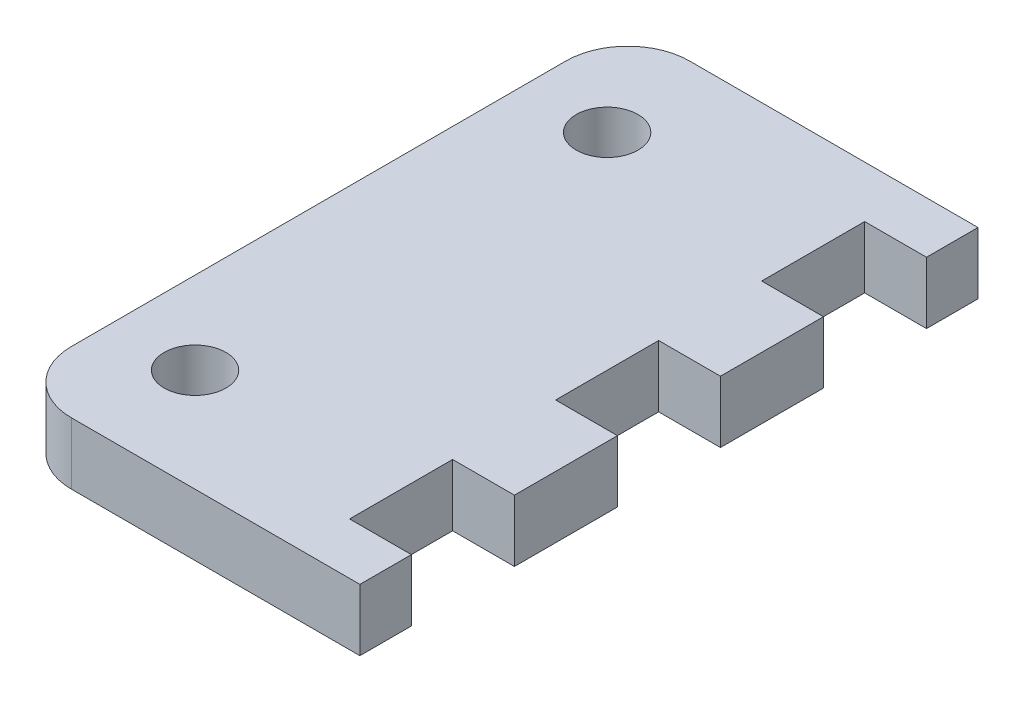
SolidWorks part; units mm, degrees
ref_plane "Front Plane" through (0, 0, 0) normal (0, 0, 1) x (1, 0, 0)
ref_plane "Top Plane" through (0, 0, 0) normal (0, 1, 0) x (1, 0, 0)
ref_plane "Right Plane" through (0, 0, 0) normal (1, 0, 0) x (0, 0, -1)
sketch "Sketch1" plane through (0, 0, 0) normal (0, 1, 0) x (1, 0, 0)
  line L1 (-8.5, 15) -> (8.5, 15)
  line L2 (-8.5, 15) -> (-8.5, -15)
  line L3 (-8.5, -15) -> (8.5, -15)
  line L4 (8.5, 15) -> (8.5, -15)
  line L5 (-8.5, 15) -> (8.5, -15) construction
  line L6 (-8.5, -15) -> (8.5, 15) construction
  point P0 (0, 0)
  dimension "D1" = 17
  dimension "D2" = 30
extrude "Boss-Extrude1" add sketch "Sketch1" along normal blind 3
sketch "Sketch2" plane through (0, 3, 0) normal (0, 1, 0) x (1, 0, 0)
  line L0 (8.5, 12.5) -> (5.5, 12.5)
  line L1 (8.5, -15) -> (8.5, 15) construction
  line L2 (5.5, 12.5) -> (5.5, 7.5)
  line L3 (5.5, 7.5) -> (8.5, 7.5)
  line L4 (8.5, 7.5) -> (8.5, 12.5)
  line L5 (8.5, 15) -> (-8.5, 15) construction
  line L6 (8.5, 2.5) -> (5.5, 2.5)
  line L7 (8.5, 2.5) -> (8.5, -2.5)
  line L8 (8.5, -2.5) -> (5.5, -2.5)
  line L9 (5.5, 2.5) -> (5.5, -2.5)
  line L10 (8.5, -7.5) -> (5.5, -7.5)
  line L11 (8.5, -7.5) -> (8.5, -12.5)
  line L12 (8.5, -12.5) -> (5.5, -12.5)
  line L13 (5.5, -7.5) -> (5.5, -12.5)
  line L14 (-8.5, -15) -> (8.5, -15) construction
  point P14 (5.5, 0)
  point P17 (5.5, 10)
  point P18 (5.5, -10)
  dimension "D1" = 5
  dimension "D2" = 5
  dimension "D3" = 5
  dimension "D4" = 15
  dimension "D5" = 5
  dimension "D6" = 5
  dimension "D7" = 3
  dimension "D8" = 3
  dimension "D9" = 3
extrude "Cut-Extrude1" cut sketch "Sketch2" against normal blind 3
sketch "Sketch3" plane through (0, 3, 0) normal (0, 1, 0) x (1, 0, 0)
  line L0 (-4.5, 17.5285) -> (-4.5, -19.8049) construction
  line L1 (-8.5, 15) -> (-8.5, -15) construction
  line L2 (8.5, 15) -> (-8.5, 15) construction
  line L3 (-8.5, -15) -> (8.5, -15) construction
  circle A0 centre (-4.5, 10) radius 1.5
  circle A1 centre (-4.5, -10) radius 1.5
  dimension "D4" = 3
  dimension "D5" = 3
  dimension "D1" = 4
  dimension "D2" = 5
  dimension "D3" = 5
extrude "Cut-Extrude2" cut sketch "Sketch3" against normal blind 3
fillet "Fillet1" radius 3 2 edges at (-8.5, 1.5, -15) (-8.5, 1.5, 15)
